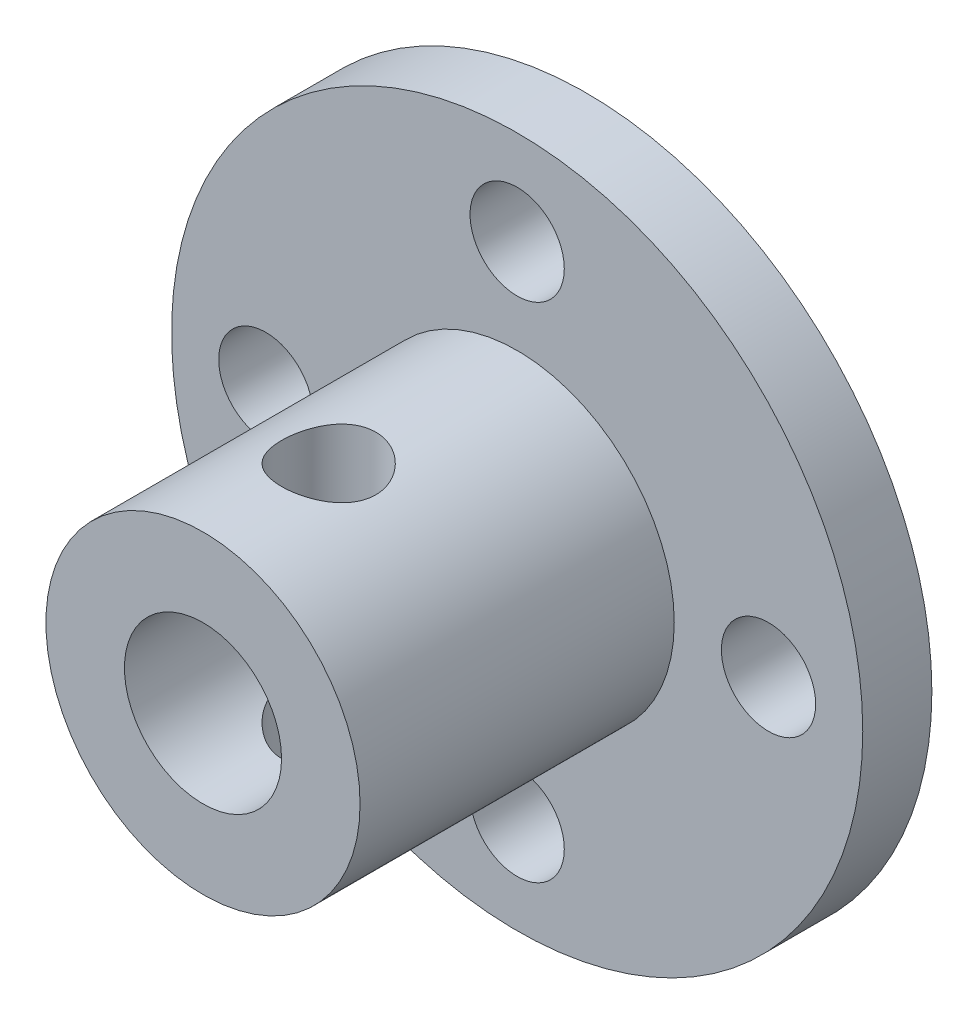
SolidWorks part; units mm, degrees
ref_plane "前视基准面" through (0, 0, 0) normal (0, 0, 1) x (1, 0, 0)
ref_plane "上视基准面" through (0, 0, 0) normal (0, 1, 0) x (1, 0, 0)
ref_plane "右视基准面" through (0, 0, 0) normal (1, 0, 0) x (0, 0, -1)
sketch "草图1" plane through (0, 0, 0) normal (0, 0, 1) x (1, 0, 0)
  circle A0 centre (0, 0) radius 11
  circle A1 centre (0, 0) radius 8 construction
  circle A2 centre (0, 8) radius 1.5
  circle A3 centre (8, 0) radius 1.5
  circle A4 centre (0, -8) radius 1.5
  circle A5 centre (-8, 0) radius 1.5
  point P15 (0, 0)
  dimension "D1" = 22
  dimension "D2" = 16
  dimension "D3" = 3
  dimension "D4" = 4
extrude "凸台-拉伸1" add sketch "草图1" along normal blind 2.2
sketch "草图2" plane through (0, 0, 2.2) normal (0, 0, 1) x (1, 0, 0)
  circle A0 centre (0, 0) radius 5
  dimension "D1" = 10
extrude "凸台-拉伸2" add sketch "草图2" along normal blind 10
sketch "草图3" plane through (0, 0, 12.2) normal (0, 0, 1) x (1, 0, 0)
  circle A0 centre (0, 0) radius 2.5
  dimension "D1" = 5
extrude "切除-拉伸1" cut sketch "草图3" against normal through all
sketch "草图4" plane through (0, 0, 0) normal (0, 1, 0) x (1, 0, 0)
  line L0 (0, 0) -> (0, -14.465)
  line L1 (-5, -2.2) -> (5, -2.2) construction
  circle A0 centre (0, -8.2) radius 1.5
  dimension "D1" = 3
  dimension "D2" = 6
extrude "切除-拉伸2" cut sketch "草图4" against normal through all both and the other way through all contours L0 A0 | L0 A0
